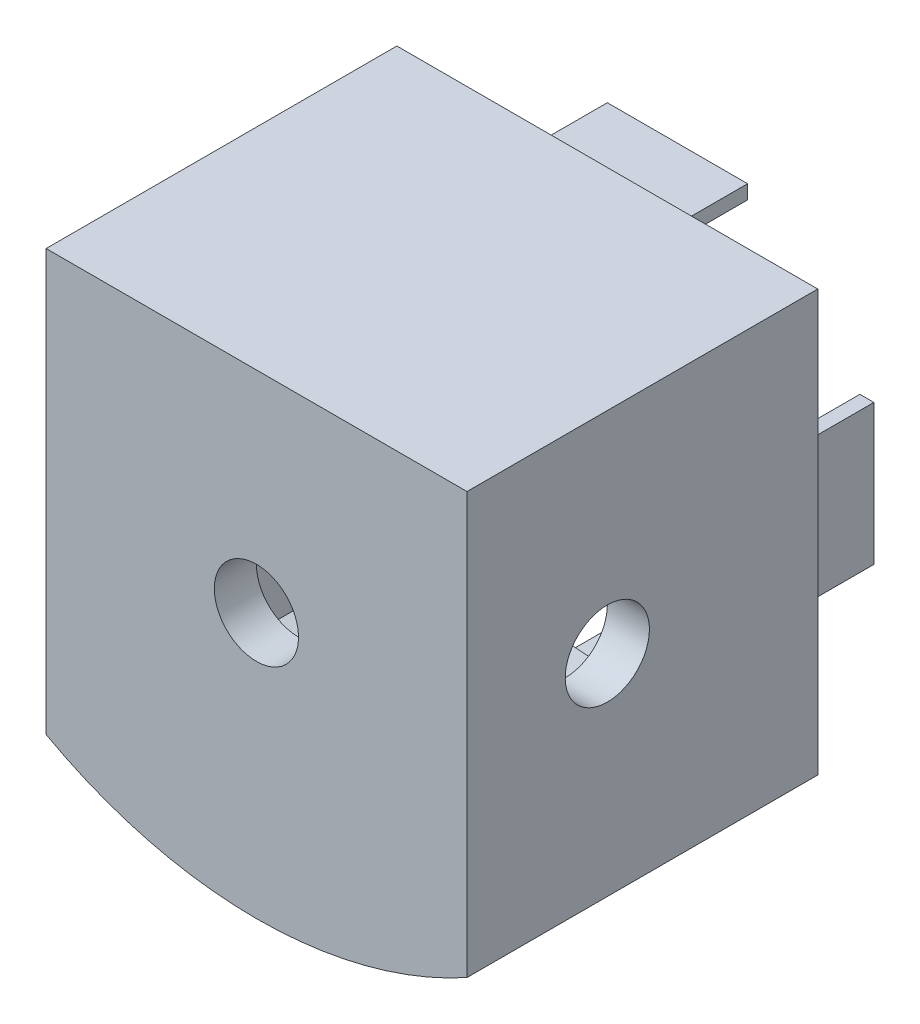
SolidWorks part; units mm, degrees
ref_plane "Front Plane" through (0, 0, 0) normal (0, 0, 1) x (1, 0, 0)
ref_plane "Top Plane" through (0, 0, 0) normal (0, 1, 0) x (1, 0, 0)
ref_plane "Right Plane" through (0, 0, 0) normal (1, 0, 0) x (0, 0, -1)
sketch "Sketch1" plane through (0, 0, 0) normal (0, 0, 1) x (1, 0, 0)
  line L2 (15, -15) -> (15, 15)
  line L3 (15, 15) -> (-15, 15)
  line L4 (-15, -15) -> (-15, 15)
  line L5 (15, -15) -> (-15, 15) construction
  line L6 (15, 15) -> (-15, -15) construction
  arc A3 (-15, -15) -> (15, -15) centre (0, 12.1293) ccw
  point P0 (0, 0)
extrude "Boss-Extrude1" add sketch "Sketch1" along normal blind 25
shell "Shell13" thickness 3
sketch "Sketch3" plane through (0, 0, 22) normal (0, 0, -1) x (-1, 0, 0)
  circle A0 centre (0.0103, 0.0076) radius 3
extrude "Cut-Extrude2" cut sketch "Sketch3" against normal blind 3
sketch "Sketch4" plane through (0, 0, 0) normal (0, 0, -1) x (-1, 0, 0)
  line L0 (12, 12) -> (12, -13.1689) construction
  line L1 (-5, 14) -> (5, 14)
  line L2 (-5, 14) -> (-5, 13)
  line L3 (-5, 13) -> (5, 13)
  line L4 (5, 14) -> (5, 13)
  line L5 (-14, 5) -> (-13, 5)
  line L6 (-14, 5) -> (-14, -5)
  line L7 (-14, -5) -> (-13, -5)
  line L8 (-13, 5) -> (-13, -5)
  line L9 (-3.5, -17) -> (3.5, -17)
  line L10 (-3.5, -17) -> (-3.5, -18)
  line L11 (-3.5, -18) -> (3.5, -18)
  line L12 (3.5, -17) -> (3.5, -18)
  line L13 (13, 5) -> (14, 5)
  line L14 (13, 5) -> (13, -5)
  line L15 (13, -5) -> (14, -5)
  line L16 (14, 5) -> (14, -5)
  line L17 (-12, -13.1689) -> (-12, 12) construction
  line L18 (-12, 12) -> (12, 12) construction
  point P16 (0, -17)
  point P18 (-13, 0)
  point P19 (13, 0)
  point P20 (0, 13)
  dimension "D1" = 1
  dimension "D2" = 1
  dimension "D3" = 1
  dimension "D4" = 17
extrude "Boss-Extrude2" add sketch "Sketch4" along normal blind 5
sketch "Sketch5" plane through (15, 0, 0) normal (1, 0, 0) x (0, 0, -1)
  line L0 (-25, 15) -> (-25, -15) construction
  circle A0 centre (-15, 0) radius 3
  point P2 (-7.2766, 0.3261)
  point P4 (0, 0)
  dimension "D1" = 10
extrude "Cut-Extrude3" cut sketch "Sketch5" against normal blind 30
